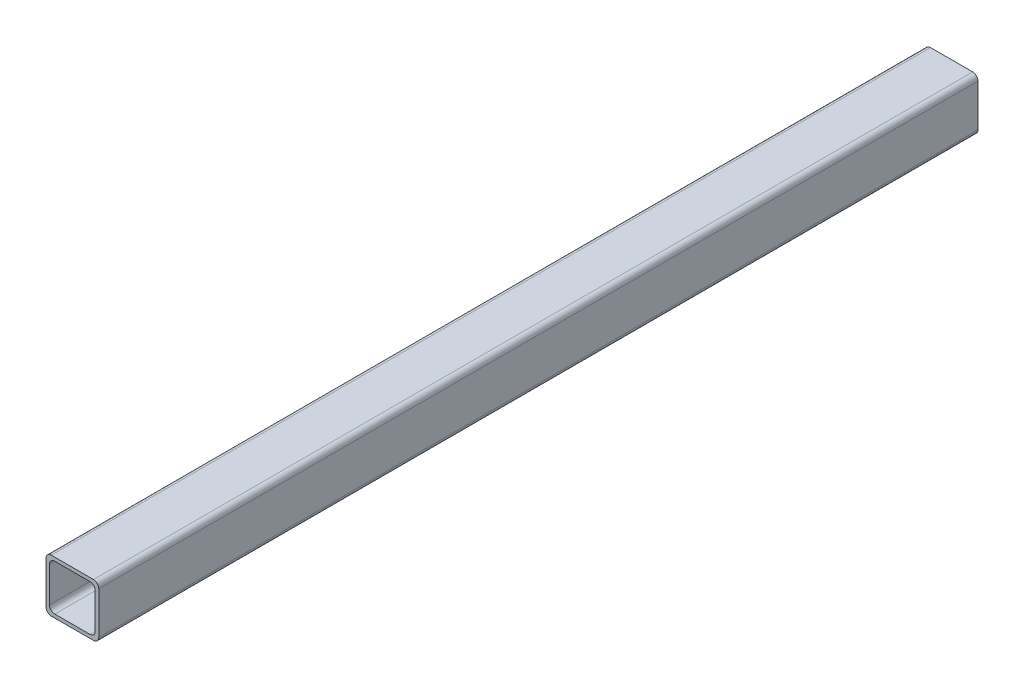
SolidWorks part; units mm, degrees
ref_plane "Plan de face" through (0, 0, 0) normal (0, 0, 1) x (1, 0, 0)
ref_plane "Plan de dessus" through (0, 0, 0) normal (0, 1, 0) x (1, 0, 0)
ref_plane "Plan de droite" through (0, 0, 0) normal (1, 0, 0) x (0, 0, -1)
sketch "Esquisse1" plane through (0, 0, 0) normal (0, 0, 1) x (1, 0, 0)
  line L1 (-12, -15) -> (12, -15)
  line L2 (-15, -12) -> (-15, 12)
  line L3 (-12, 15) -> (12, 15)
  line L4 (15, -12) -> (15, 12)
  line L5 (0, 15) -> (0, -15) construction
  line L6 (-15, 0) -> (15, 0) construction
  line L7 (-10, -13) -> (10, -13)
  line L8 (-13, -10) -> (-13, 10)
  line L9 (-10, 13) -> (10, 13)
  line L10 (13, -10) -> (13, 10)
  line L11 (0, 13) -> (0, -13) construction
  line L12 (-13, 0) -> (13, 0) construction
  arc A0 (10, -13) -> (13, -10) centre (10, -10) ccw
  arc A1 (12, -15) -> (15, -12) centre (12, -12) ccw
  arc A2 (-13, 10) -> (-10, 13) centre (-10, 10) cw
  arc A3 (-10, -13) -> (-13, -10) centre (-10, -10) cw
  arc A4 (10, 13) -> (13, 10) centre (10, 10) cw
  arc A5 (-15, 12) -> (-12, 15) centre (-12, 12) cw
  arc A6 (-12, -15) -> (-15, -12) centre (-12, -12) cw
  arc A7 (12, 15) -> (15, 12) centre (12, 12) cw
  point P0 (0, 0)
  point P4 (0, 0)
  point P13 (13, -13)
  point P21 (-13, 13)
  point P24 (-13, -13)
  dimension "D5" = 3
  dimension "D1" = 30
  dimension "D2" = 26
  dimension "D3" = 30
  dimension "D4" = 26
extrude "Boss.-Extru.1" add sketch "Esquisse1" against normal blind 500
